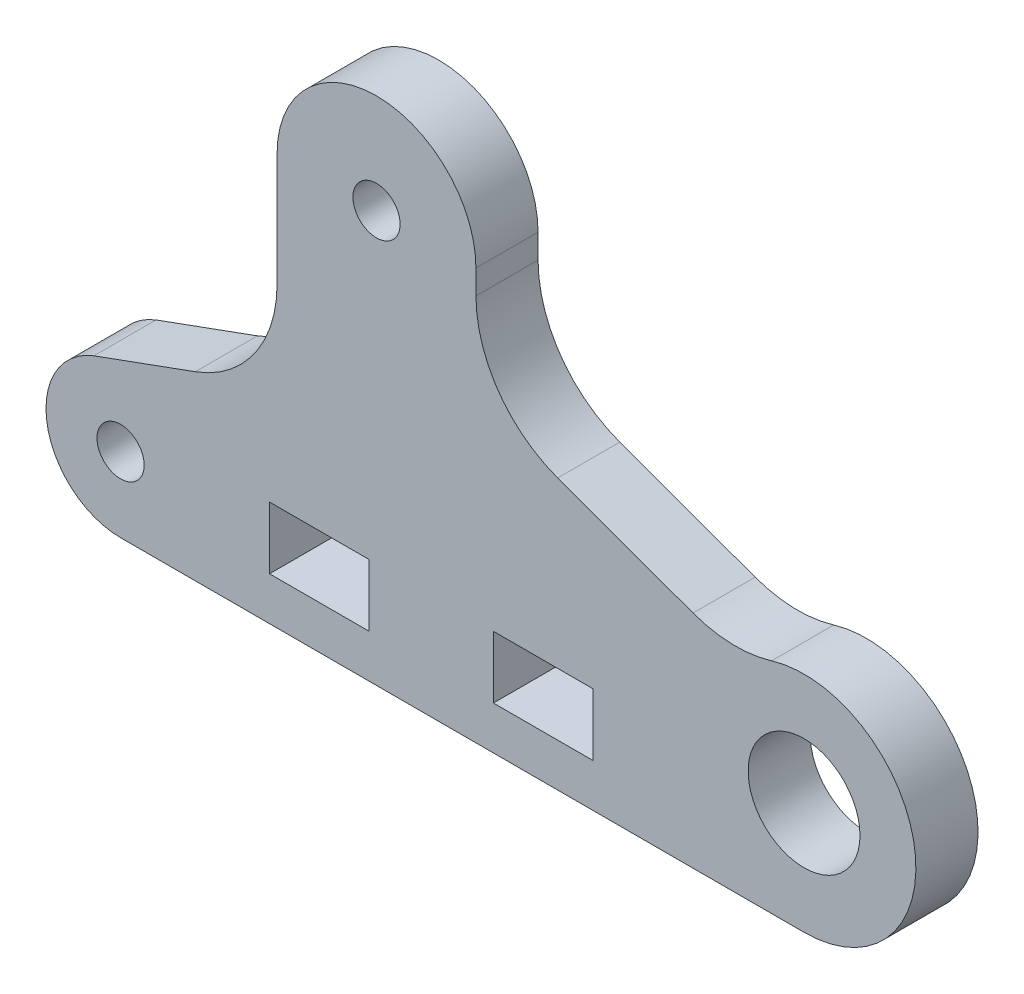
SolidWorks part; units mm, degrees
ref_plane "Plan de face" through (0, 0, 0) normal (0, 0, 1) x (1, 0, 0)
ref_plane "Plan de dessus" through (0, 0, 0) normal (0, 1, 0) x (1, 0, 0)
ref_plane "Plan de droite" through (0, 0, 0) normal (1, 0, 0) x (0, 0, -1)
sketch "Esquisse1" plane through (0, 0, 0) normal (0, 0, 1) x (1, 0, 0)
  line L0 (1, -17.0648) -> (9, -17.0648)
  line L1 (9, -17.0648) -> (9, -12.0648)
  line L2 (9, -12.0648) -> (1, -12.0648)
  line L3 (1, -17.0648) -> (1, -12.0648)
  line L4 (-17, -12.0648) -> (-17.0139, -17.0648)
  line L5 (-9, -12.0648) -> (-9, -17.0648)
  line L6 (-22.9842, -5.9701) -> (-31.1458, -8.9416)
  line L7 (-16.4044, 12.5454) -> (-16.4044, 3.4268)
  line L8 (-0.4044, 10.6015) -> (-0.4044, 12.5454)
  line L9 (17.0661, -2.7593) -> (6.1754, 1.2046)
  line L10 (-29, -20.5448) -> (26, -20.5448)
  line L11 (-17.0139, -17.0648) -> (-9, -17.0648)
  line L12 (-9, -12.0648) -> (-17, -12.0648)
  arc A0 (-22.9842, -5.9701) -> (-16.4044, 3.4268) centre (-26.4044, 3.4268) ccw
  arc A1 (-0.4044, 10.6015) -> (6.1754, 1.2046) centre (9.5956, 10.6015) ccw
  arc A2 (17.0661, -2.7593) -> (23.3883, -2.9321) centre (20.4863, 6.6376) ccw
  circle A3 centre (-8.4044, 12.5454) radius 1.9
  circle A4 centre (-29, -14.5448) radius 1.9
  arc A6 (-0.4044, 12.5454) -> (-16.4044, 12.5454) centre (-8.4044, 12.5454) ccw
  arc A7 (26, -20.5448) -> (23.3883, -2.9321) centre (26, -11.5448) ccw
  arc A8 (-31.1458, -8.9416) -> (-29, -20.5448) centre (-29, -14.5448) ccw
  circle A9 centre (26, -11.5448) radius 4.5
  dimension "D1" = 8
  dimension "D2" = 6
  dimension "D3" = 9
  dimension "D4" = 10
  dimension "D5" = 10
  dimension "D6" = 10
  dimension "D7" = 3.8
  dimension "D8" = 3.8
  dimension "D9" = 9
  dimension "D10" = 8
  dimension "D11" = 8
  dimension "D12" = 5
  dimension "D14" = 3.48
  dimension "D15" = 10
extrude "Boss.-Extru.1" add sketch "Esquisse1" along normal blind 5
